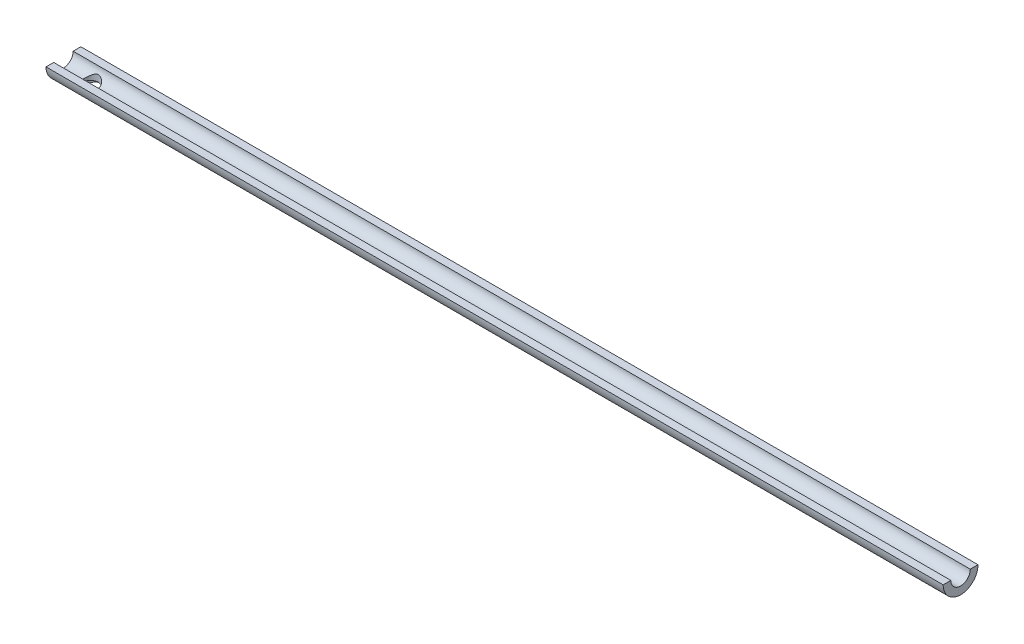
SolidWorks part; units mm, degrees
ref_plane "Front Plane" through (0, 0, 0) normal (0, 0, 1) x (1, 0, 0)
ref_plane "Top Plane" through (0, 0, 0) normal (0, 1, 0) x (1, 0, 0)
ref_plane "Right Plane" through (0, 0, 0) normal (1, 0, 0) x (0, 0, -1)
sketch "Sketch1" plane through (0, 0, 0) normal (0, 1, 0) x (1, 0, 0)
  line L1 (0, 0) -> (735.584, 0)
  line L2 (0, 0) -> (0, 38.1)
  line L3 (0, 38.1) -> (735.584, 38.1)
  line L4 (735.584, 0) -> (735.584, 38.1)
  dimension "blank_length" = 735.584
  dimension "blank_width" = 38.1
extrude "wood block" add sketch "Sketch1" along normal blind 19.05
sketch "Sketch2" plane through (735.584, 0, 0) normal (1, 0, 0) x (0, 0, -1)
  line L0 (0, 19.05) -> (38.1, 19.05) construction
  circle A0 centre (19.05, 19.05) radius 7.9756
  dimension "inner_diameter" = 15.9512
extrude "inner bore" cut sketch "Sketch2" against normal through all
sketch "Sketch3" plane through (0, 0, 0) normal (0, 1, 0) x (1, 0, 0)
  line L0 (0, 19.05) -> (22.225, 19.05) construction
  line L1 (0, 27.0256) -> (0, 11.0744) construction
  circle A0 centre (22.225, 19.05) radius 6.3881
  point P3 (15.8369, 19.05)
  dimension "mouthpiece_through_hole" = 12.7762
  dimension "mouthpiece_location" = 22.225
extrude "mouthpiece through hole" cut sketch "Sketch3" along normal through all
sketch "Sketch5" plane through (0, 0, 0) normal (0, -1, 0) x (1, 0, 0)
  line L0 (367.792, 0) -> (367.792, -38.1) construction
  line L1 (0, 0) -> (735.584, 0) construction
  line L2 (735.584, -38.1) -> (0, -38.1) construction
  circle A0 centre (22.225, -19.05) radius 8.128
  circle A1 centre (713.359, -19.05) radius 8.128
  dimension "tube_diameter" = 16.256
extrude "counterbore" cut sketch "Sketch5" against normal blind 8.89
sketch "Sketch4" plane through (0, 0, 0) normal (-1, 0, 0) x (0, 0, 1)
  circle A0 centre (-19.05, 19.05) radius 14.2875
  arc A1 (-27.0256, 19.05) -> (-11.0744, 19.05) centre (-19.05, 19.05) ccw construction
  dimension "outer_diameter" = 28.575
extrude "outer diameter" cut sketch "Sketch4" against normal through all flip side to cut
equation "\"g_mp_block_OD\"= 28.575mm"
equation "\"g_mp_block_ID\"= 15.875mm"
equation "\"g_mp_block_L_blank\"= 735.584mm"
equation "\"g_mp_block_blank_W\"= 38.1mm"
equation "\"g_mp_tube_OD\"= 15.875mm"
equation "\"g_thru_passage_OD\"= 12.7mm"
equation "\"c_glue_gap\"= 0.0762mm"
equation "\"g_slip_fit\"= 0.381mm"
equation "\"thickness@wood block\"= \"g_mp_block_blank_W\" / 2"
equation "\"blank_length@Sketch1\"= \"g_mp_block_L_blank\""
equation "\"blank_width@Sketch1\"= \"g_mp_block_blank_W\""
equation "\"outer_diameter@Sketch4\"= \"g_mp_block_OD\""
equation "\"inner_diameter@Sketch2\"= \"g_mp_block_ID\" + \"c_glue_gap\""
equation "\"mouthpiece_through_hole@Sketch3\"= \"g_thru_passage_OD\" + \"c_glue_gap\""
